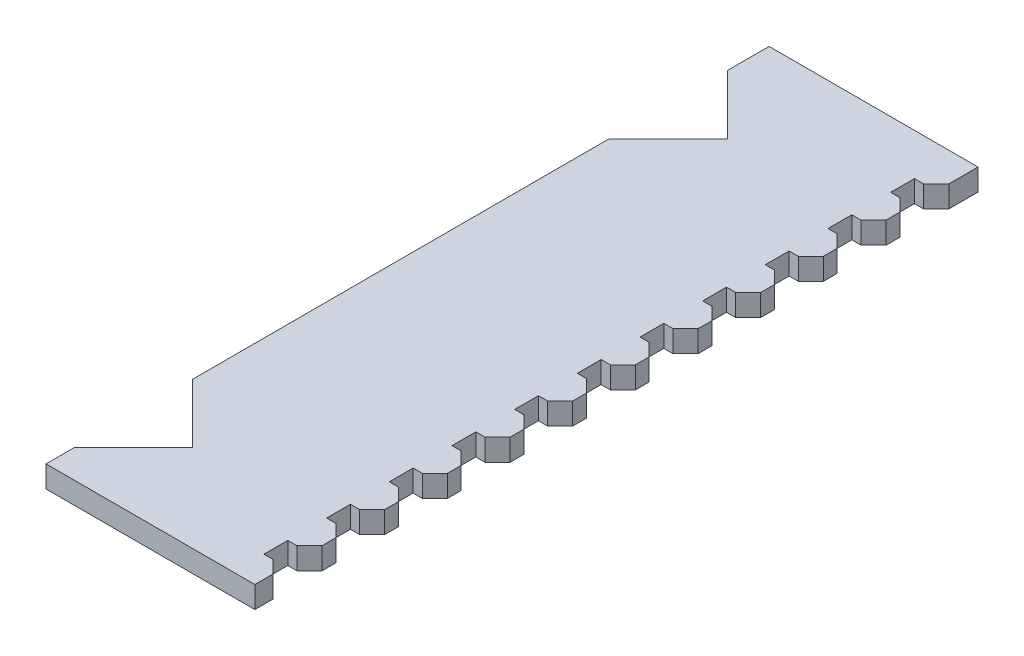
SolidWorks part; units mm, degrees
ref_plane "Front Plane" through (0, 0, 0) normal (0, 0, 1) x (1, 0, 0)
ref_plane "Top Plane" through (0, 0, 0) normal (0, 1, 0) x (1, 0, 0)
ref_plane "Right Plane" through (0, 0, 0) normal (1, 0, 0) x (0, 0, -1)
sketch "Sketch1" plane through (0, 0, 0) normal (0, 1, 0) x (1, 0, 0)
  line L1 (0, 0) -> (50, 0)
  line L2 (0, 0) -> (0, 173.07)
  line L3 (0, 173.07) -> (50, 173.07)
  line L4 (50, 0) -> (50, 173.07)
  dimension "D1" = 173.07
  dimension "D2" = 50
extrude "Boss-Extrude1" add sketch "Sketch1" along normal blind 5.2
sketch "Sketch2" plane through (0, 5.2, 0) normal (0, 1, 0) x (1, 0, 0)
  line L0 (0, 134.7857) -> (14.1421, 148.9279)
  line L1 (0, 173.07) -> (0, 0) construction
  line L2 (14.1421, 148.9279) -> (0, 163.07)
  line L3 (0, 86.535) -> (50, 86.535) construction
  line L4 (50, 0) -> (50, 173.07) construction
  line L5 (14.1421, 20.9279) -> (0, 6.7857)
  line L6 (0, 35.07) -> (14.1421, 20.9279)
  line L7 (0, 163.07) -> (0, 134.7857)
  line L8 (0, 35.07) -> (0, 6.7857)
  dimension "D1" = 45
  dimension "D2" = 10
  dimension "D3" = 20
  dimension "D4" = 128
  dimension "D5" = 45
  dimension "D6" = 45
extrude "Cut-Extrude1" cut sketch "Sketch2" against normal blind 6
sketch "Sketch4" plane through (0, 5.2, 0) normal (0, 1, 0) x (1, 0, 0)
  line L0 (50, 0) -> (50, 173.07) construction
  line L1 (50, 163.07) -> (44.8, 163.07)
  line L2 (50, 163.07) -> (50, 157.37)
  line L3 (50, 157.37) -> (44.8, 157.37)
  line L4 (44.8, 163.07) -> (44.8, 157.37)
  line L5 (50, 173.07) -> (0, 173.07) construction
  dimension "D1" = 5.2
  dimension "D2" = 5.7
  dimension "D3" = 10
extrude "Cut-Extrude2" cut sketch "Sketch4" against normal blind 6
chamfer "Chamfer1" distance 3 angle 45 2 edges at (50, 2.6, -163.07) (50, 2.6, -157.37)
pattern_linear "LPattern1" count 11 spacing 15 along (0, 0, 1) of "Chamfer1", "Cut-Extrude2"
equation "\"depth\" = 5.2"
equation "\"D1@Boss-Extrude1\"=\"depth\""
equation "\"D1@Sketch4\"=\"depth\""
equation "\"width\"= 5.7"
equation "\"D2@Sketch4\"=\"width\""
